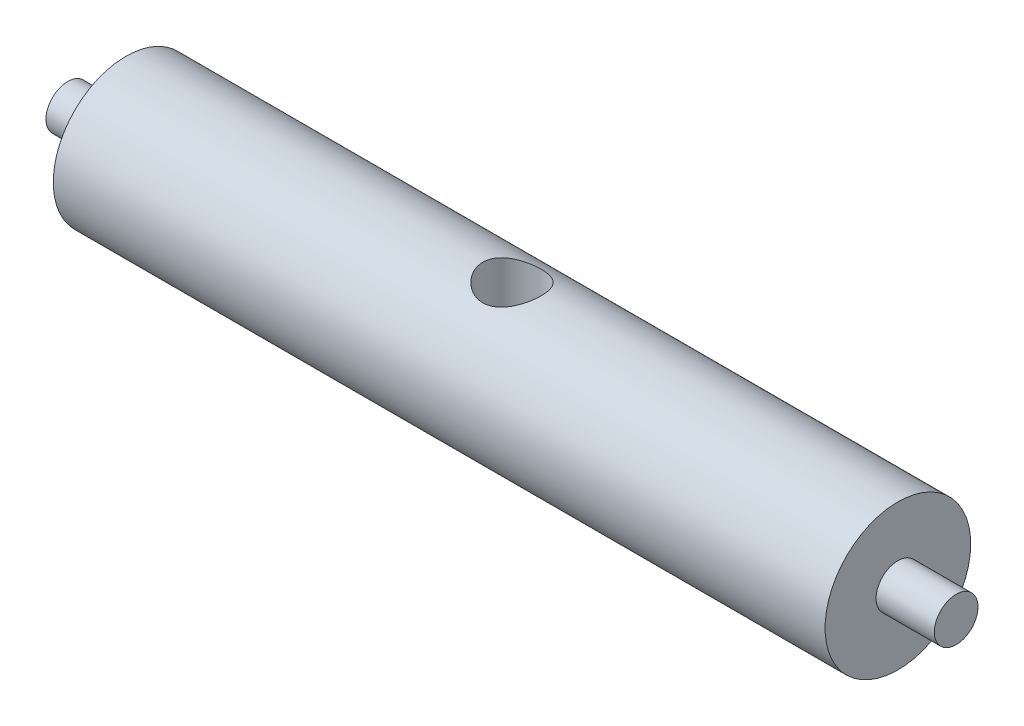
SolidWorks part; units mm, degrees
ref_plane "Front Plane" through (0, 0, 0) normal (1, 0, 0) x (0, 1, 0)
ref_plane "Top Plane" through (0, 0, 0) normal (0, 0, 1) x (0, 1, 0)
ref_plane "Right Plane" through (0, 0, 0) normal (0, 1, 0) x (-1, 0, 0)
sketch "Sketch1" plane through (0, 0, 0) normal (0, 1, 0) x (-1, 0, 0)
  line L0 (-170, 0) -> (170, 0) construction
  line L1 (-161.3299, 0) -> (-161.3299, 7.5)
  line L2 (-161.3299, 7.5) -> (-141.3299, 7.5)
  line L3 (-141.3299, 7.5) -> (-141.3299, 25)
  line L4 (-141.3299, 25) -> (123.6701, 25)
  line L5 (123.6701, 25) -> (123.6701, 7.5)
  line L6 (123.6701, 7.5) -> (143.6701, 7.5)
  line L7 (143.6701, 7.5) -> (143.6701, 0)
  line L8 (-161.3299, 0) -> (143.6701, 0)
  point P1 (0, 0)
  dimension "D1" = 15
  dimension "D2" = 50
  dimension "D3" = 20
  dimension "D4" = 265
revolve "Revolve1" add sketch "Sketch1" angle 360 about L0
sketch "Sketch2" plane through (0, 0, 0) normal (0, 1, 0) x (-1, 0, 0)
  line L0 (-141.3299, 0) -> (123.6701, 0) construction
  line L1 (-141.3299, 25) -> (-141.3299, -25) construction
  line L2 (123.6701, -25) -> (123.6701, 25) construction
  line L3 (-8.8299, 25) -> (-8.8299, -25) construction
  line L4 (123.6701, 25) -> (-141.3299, 25) construction
  line L5 (-141.3299, -25) -> (123.6701, -25) construction
  circle A0 centre (-8.8299, 0) radius 10
  dimension "D1" = 20
extrude "Cut-Extrude1" cut sketch "Sketch2" against normal through all and the other way through all
